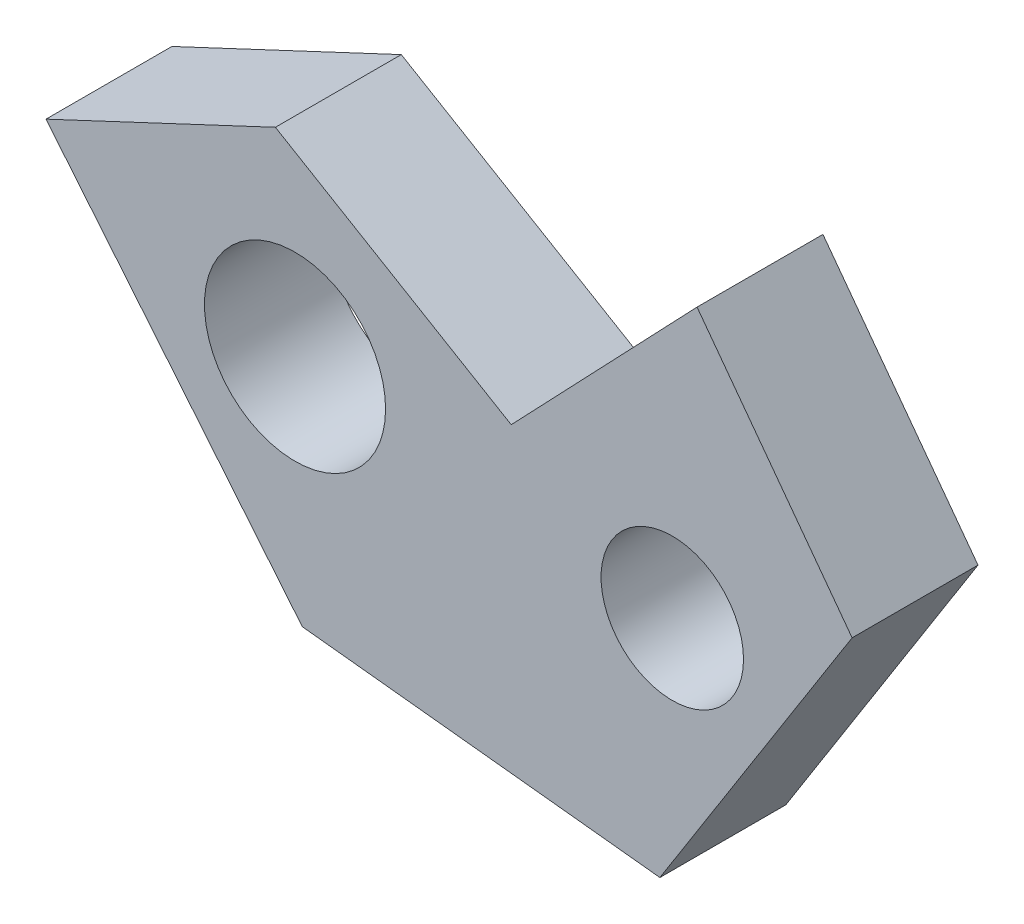
SolidWorks part; units mm, degrees
ref_plane "Front Plane" through (0, 0, 0) normal (0, 0, 1) x (1, 0, 0)
ref_plane "Top Plane" through (0, 0, 0) normal (0, 1, 0) x (1, 0, 0)
ref_plane "Right Plane" through (0, 0, 0) normal (1, 0, 0) x (0, 0, -1)
sketch "Sketch1" plane through (0, 0, 0) normal (0, 0, 1) x (1, 0, 0)
  line L0 (-147.8193, 6.1082) -> (-74.9277, 40.3143)
  line L1 (-74.9277, 40.3143) -> (0, -4.0722)
  line L2 (0, -4.0722) -> (59.0463, 57.8246)
  line L3 (59.0463, 57.8246) -> (108.3194, -8.5515)
  line L4 (108.3194, -8.5515) -> (47.237, -105.0616)
  line L5 (47.237, -105.0616) -> (-66.3761, -92.8452)
  line L6 (-66.3761, -92.8452) -> (-147.8193, 6.1082)
extrude "Boss-Extrude1" add sketch "Sketch1" along normal blind 40
sketch "Sketch2" plane through (0, 0, 40) normal (0, 0, 1) x (1, 0, 0)
  circle A0 centre (51.1795, -31.7322) radius 22.6318
  circle A1 centre (-68.6954, -19.7033) radius 28.7765
extrude "Cut-Extrude2" cut sketch "Sketch2" against normal up to surface (40 mm away) up to face at (-10.6458, -15.1833, 0)
